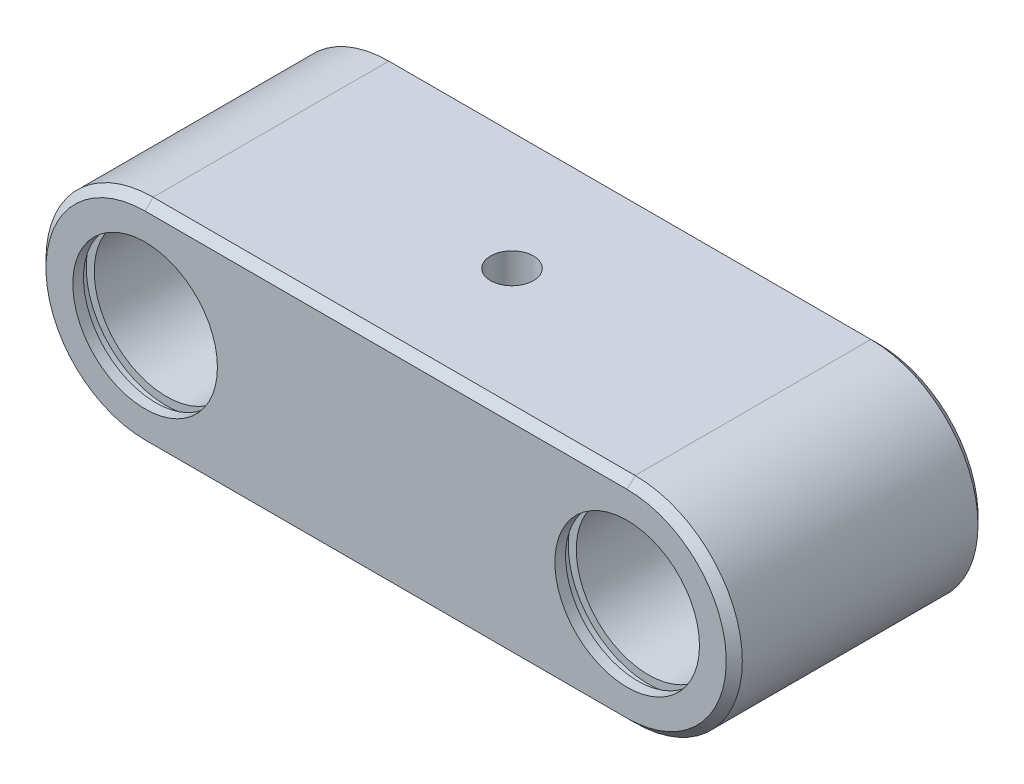
SolidWorks part; units mm, degrees
ref_plane "Front Plane" through (0, 0, 0) normal (0, 0, 1) x (1, 0, 0)
ref_plane "Top Plane" through (0, 0, 0) normal (0, 1, 0) x (1, 0, 0)
ref_plane "Right Plane" through (0, 0, 0) normal (1, 0, 0) x (0, 0, -1)
sketch "Sketch1" plane through (0, 0, 0) normal (0, 0, 1) x (1, 0, 0)
  line L0 (-45, 0) -> (45, 0) construction
  line L1 (-45, 20) -> (45, 20)
  line L2 (-45, -20) -> (45, -20)
  circle A0 centre (-45, 0) radius 13.5
  circle A1 centre (45, 0) radius 13.5
  arc A2 (-45, 20) -> (-45, -20) centre (-45, 0) ccw
  arc A3 (45, -20) -> (45, 20) centre (45, 0) ccw
  point P4 (0, 0)
  dimension "D1" = 27
  dimension "D2" = 27
  dimension "D3" = 45
  dimension "D4" = 45
  dimension "D5" = 40
extrude "Boss-Extrude1" add sketch "Sketch1" against normal blind 47 from offset 650
sketch "Sketch4" plane through (0, 0, 650) normal (0, 0, 1) x (1, 0, 0)
  circle A0 centre (-45, 0) radius 15
  circle A1 centre (45, 0) radius 15
  circle A2 centre (45, 0) radius 13.5 construction
  circle A3 centre (-45, 0) radius 13.5 construction
  circle A4 centre (45, 0) radius 13.5
  circle A5 centre (-45, 0) radius 13.5
  dimension "D1" = 30
  dimension "D2" = 30
extrude "Cut-Extrude2" cut sketch "Sketch4" against normal blind 2 from offset 2 offset against normal yes
sketch "Sketch5" plane through (0, 20, 0) normal (0, 1, 0) x (1, 0, 0)
  line L2 (45, -603) -> (-45, -603) construction
  circle A1 centre (0, -626.5) radius 4
  dimension "D1" = 23.5
  dimension "D2" = 8
extrude "Cut-Extrude3" cut sketch "Sketch5" against normal blind 40
sketch "Sketch6" plane through (0, 0, 603) normal (0, 0, -1) x (-1, 0, 0)
  circle A0 centre (-45, 0) radius 15
  circle A1 centre (45, 0) radius 15
  circle A2 centre (45, 0) radius 13.5 construction
  circle A3 centre (-45, 0) radius 13.5 construction
  circle A4 centre (45, 0) radius 13.5
  circle A5 centre (-45, 0) radius 13.5
  dimension "D1" = 30
  dimension "D2" = 30
extrude "Cut-Extrude4" cut sketch "Sketch6" against normal blind 2 from offset 2 offset against normal yes
chamfer "Chamfer1" distance 1.5 angle 45 8 edges at (0, -20, 603) (65, 0, 603) (-65, 0, 603) (0, 20, 603) (0, -20, 650) (65, 0, 650) (-65, 0, 650) (0, 20, 650)
